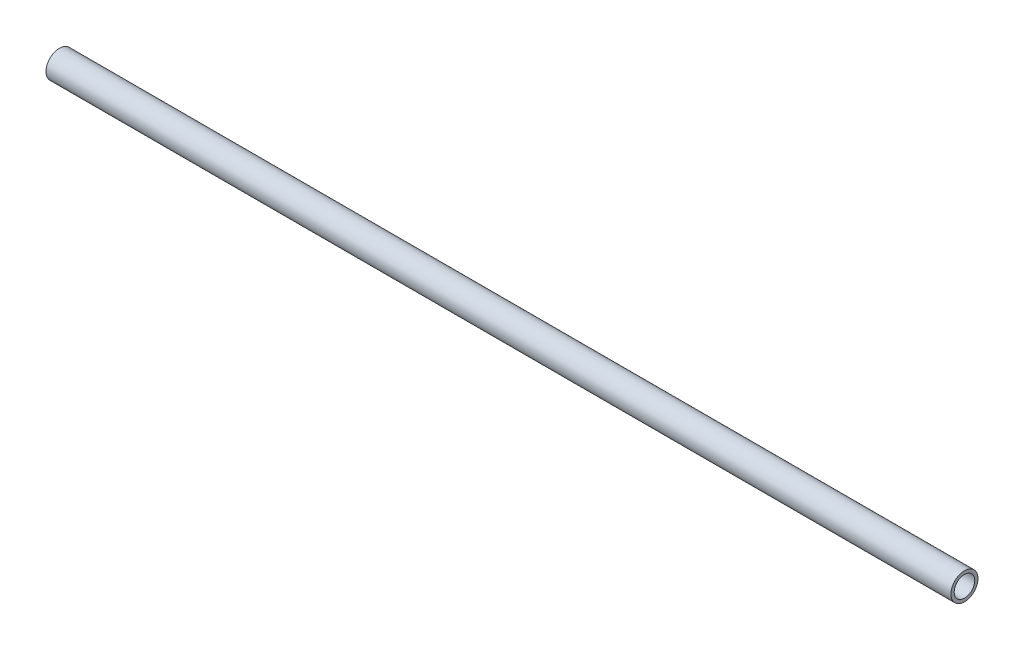
SolidWorks part; units mm, degrees
material "AISI 4130 Steel, annealed at 865C"
ref_plane "Front Plane" through (0, 0, 0) normal (0, 0, 1) x (1, 0, 0)
ref_plane "Top Plane" through (0, 0, 0) normal (0, 1, 0) x (1, 0, 0)
ref_plane "Right Plane" through (0, 0, 0) normal (1, 0, 0) x (0, 0, -1)
sketch "Sketch1" plane through (0, 0, 0) normal (1, 0, 0) x (0, 0, -1)
  circle A0 centre (0, 0) radius 12.7
  circle A1 centre (0, 0) radius 9.652
  dimension "D1" = 25.4
  dimension "D2" = 19.304
extrude "Boss-Extrude1" add sketch "Sketch1" along normal blind 850
